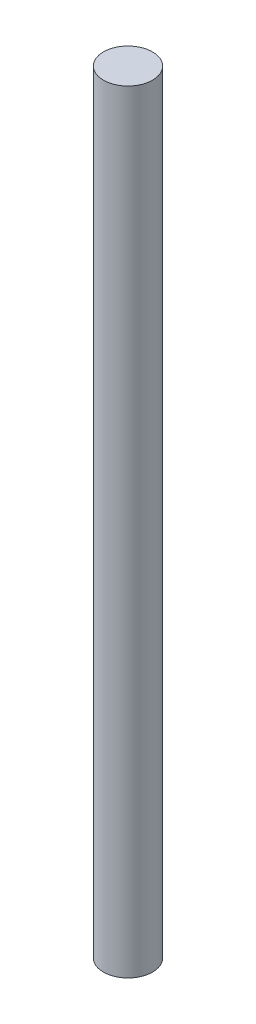
SolidWorks part; units mm, degrees
ref_plane "Front" through (0, 0, 0) normal (0, 0, 1) x (1, 0, 0)
ref_plane "Top" through (0, 0, 0) normal (0, 1, 0) x (1, 0, 0)
ref_plane "Right" through (0, 0, 0) normal (1, 0, 0) x (0, 0, -1)
sketch "Sketch1" plane through (0, 0, 0) normal (0, 1, 0) x (1, 0, 0)
  circle A0 centre (0, 0) radius 3.175
  dimension "D1" = 6.35
extrude "Boss-Extrude1" add sketch "Sketch1" along normal blind 100
